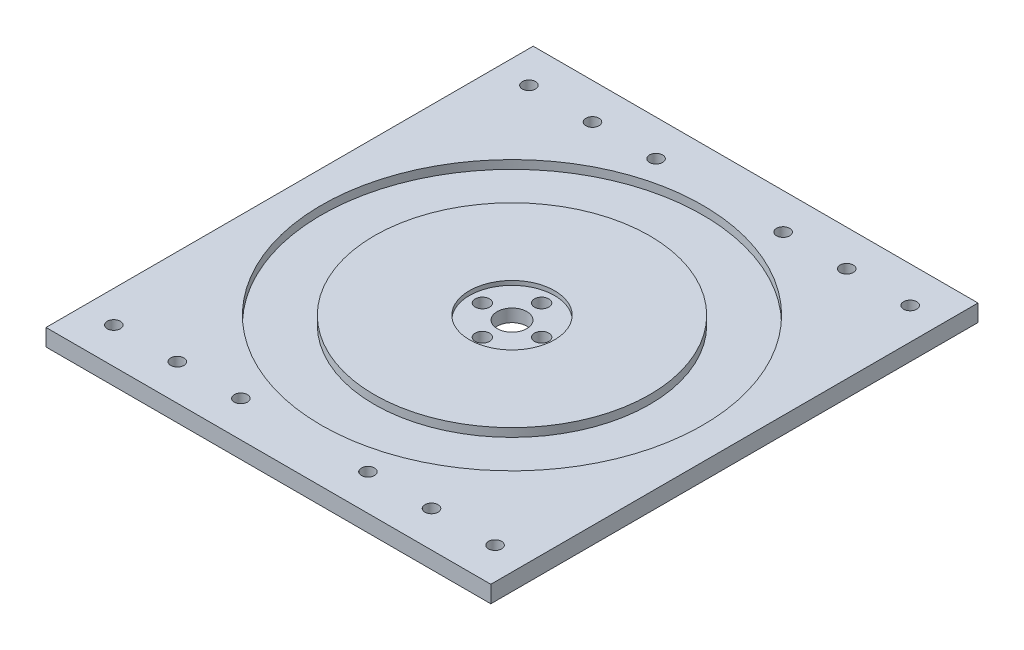
SolidWorks part; units mm, degrees
ref_plane "前视基准面" through (0, 0, 0) normal (0, 0, 1) x (1, 0, 0)
ref_plane "上视基准面" through (0, 0, 0) normal (0, 1, 0) x (1, 0, 0)
ref_plane "右视基准面" through (0, 0, 0) normal (1, 0, 0) x (0, 0, -1)
other "Configuration Table"
sketch "草图1" plane through (0, 0, 0) normal (0, 1, 0) x (1, 0, 0)
  line L0 (-93.4397, 0) -> (118.7468, 0) construction
  line L1 (-52.5, -57.5) -> (52.5, -57.5)
  line L2 (-52.5, -57.5) -> (-52.5, 57.5)
  line L3 (-52.5, 57.5) -> (52.5, 57.5)
  line L4 (52.5, -57.5) -> (52.5, 57.5)
  line L5 (-52.5, -57.5) -> (52.5, 57.5) construction
  line L6 (-52.5, 57.5) -> (52.5, -57.5) construction
  line L7 (0, 92.3971) -> (0, -129.74) construction
  circle A0 centre (0, 0) radius 45.1 construction
  circle A1 centre (0, 0) radius 3.5
  circle A2 centre (45, 49) radius 1.55
  circle A3 centre (45, -49) radius 1.55
  circle A4 centre (-45, -49) radius 1.55
  circle A5 centre (-45, 49) radius 1.55
  circle A6 centre (-15, -49) radius 1.55
  circle A7 centre (15, -49) radius 1.55
  circle A8 centre (15, 49) radius 1.55
  circle A9 centre (-15, 49) radius 1.55
  circle A10 centre (30, 49) radius 1.55
  circle A11 centre (-30, 49) radius 1.55
  circle A12 centre (-30, -49) radius 1.55
  circle A13 centre (30, -49) radius 1.55
  point P0 (0, 0)
  dimension "D3" = 90.2
  dimension "D4" = 7
  dimension "D7" = 3.1
  dimension "D9" = 3.1
  dimension "D1" = 105
  dimension "D2" = 115
  dimension "D5" = 98
  dimension "D6" = 90
  dimension "D8" = 30
extrude "凸台-拉伸1" add sketch "草图1" along normal blind 4
sketch "草图2" plane through (0, 4, 0) normal (0, 1, 0) x (1, 0, 0)
  circle A0 centre (0, 0) radius 45
  circle A1 centre (0, 0) radius 32.5
  dimension "D1" = 90
  dimension "D2" = 65
extrude "切除-拉伸1" cut sketch "草图2" against normal blind 2
sketch "草图3" plane through (0, 4, 0) normal (0, 1, 0) x (1, 0, 0)
  circle A0 centre (0, 0) radius 10.05
  circle A1 centre (0, 0) radius 7 construction
  circle A2 centre (0, 7) radius 1.7
  circle A4 centre (7, 0) radius 1.7
  circle A5 centre (0, -7) radius 1.7
  circle A6 centre (-7, 0) radius 1.7
  point P17 (0, 0)
  dimension "D1" = 20.1
  dimension "D2" = 14
  dimension "D3" = 3.4
  dimension "D4" = 4
extrude "切除-拉伸2" cut sketch "草图3" against normal blind 1
sketch "草图4" plane through (0, 3, 0) normal (0, 1, 0) x (1, 0, 0)
  circle A1 centre (7, 0) radius 1.7 construction
  circle A3 centre (7, 0) radius 1.7
  circle A4 centre (0, 7) radius 1.7 construction
  circle A5 centre (0, -7) radius 1.7 construction
  circle A6 centre (-7, 0) radius 1.7 construction
  circle A7 centre (0, 7) radius 1.7
  circle A8 centre (0, -7) radius 1.7
  circle A9 centre (-7, 0) radius 1.7
extrude "切除-拉伸5" cut sketch "草图4" against normal blind 20 and the other way blind 20
sketch "草图5" plane through (0, 4, 0) normal (0, 1, 0) x (1, 0, 0)
  line L0 (0, 0) -> (-29.8716, 29.8716) construction
  line L1 (0, 0) -> (0, 18.399) construction
  dimension "D1" = 45
